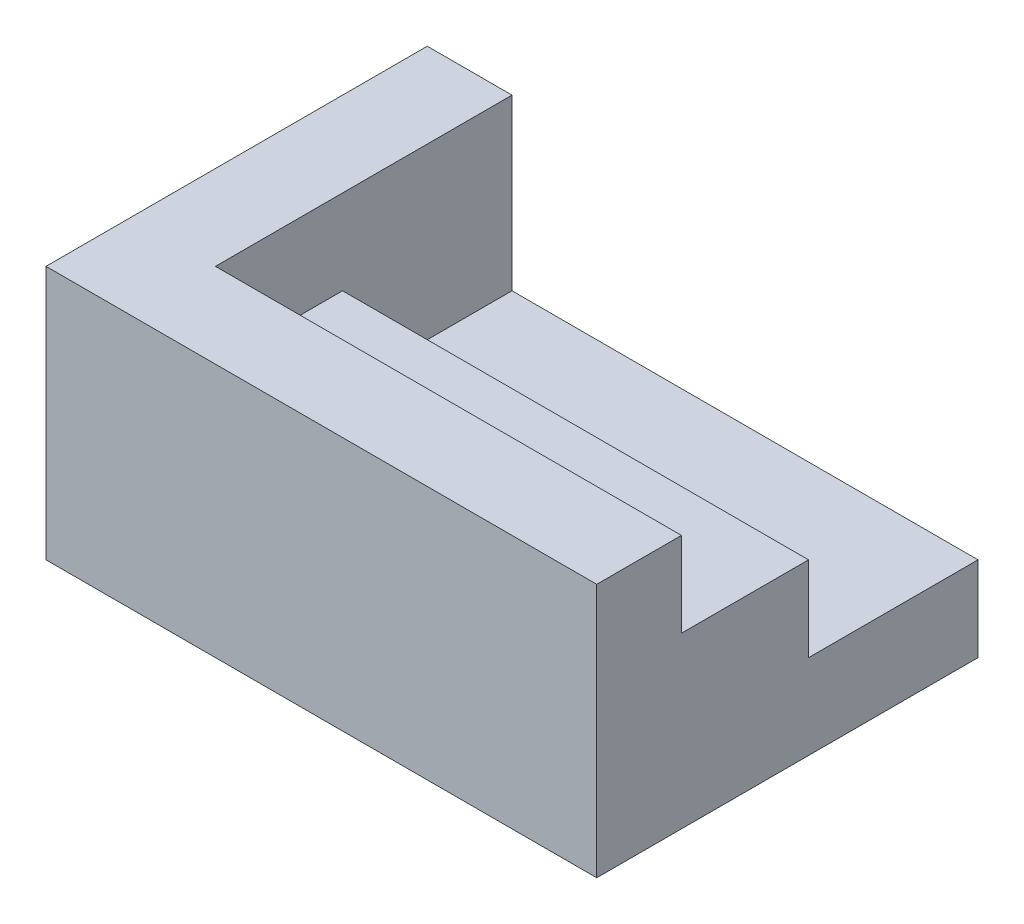
SolidWorks part; units mm, degrees
ref_plane "Front Plane" through (0, 0, 0) normal (0, 0, 1) x (1, 0, 0)
ref_plane "Top Plane" through (0, 0, 0) normal (0, 1, 0) x (1, 0, 0)
ref_plane "Right Plane" through (0, 0, 0) normal (1, 0, 0) x (0, 0, -1)
sketch "Sketch1" plane through (0, 0, 0) normal (0, 1, 0) x (1, 0, 0)
  line L1 (0, 0) -> (104, 0)
  line L2 (0, 0) -> (0, 72)
  line L3 (0, 72) -> (104, 72)
  line L4 (104, 0) -> (104, 72)
  dimension "D1" = 72
  dimension "D2" = 104
extrude "Boss-Extrude1" add sketch "Sketch1" along normal blind 16
sketch "Sketch3" plane through (0, 0, 0) normal (-1, 0, 0) x (0, 0, 1)
  line L1 (0, 0) -> (-16, 0)
  line L2 (0, 0) -> (0, 48)
  line L3 (0, 48) -> (-16, 48)
  line L4 (-16, 0) -> (-16, 48)
  dimension "D1" = 48
  dimension "D2" = 16
extrude "Boss-Extrude2" add sketch "Sketch3" against normal blind 104
sketch "Sketch6" plane through (0, 0, -72) normal (0, 0, -1) x (-1, 0, 0)
  line L1 (0, 0) -> (-16, 0)
  line L2 (0, 0) -> (0, 48)
  line L3 (0, 48) -> (-16, 48)
  line L4 (-16, 0) -> (-16, 48)
  dimension "D1" = 16
  dimension "D2" = 48
extrude "Boss-Extrude3" add sketch "Sketch6" against normal blind 72
sketch "Sketch7" plane through (0, 16, 0) normal (0, 1, 0) x (1, 0, 0)
  line L0 (104, 16) -> (104, 72) construction
  line L1 (16, 16) -> (104, 16)
  line L2 (16, 16) -> (16, 40)
  line L3 (16, 40) -> (104, 40)
  line L4 (104, 16) -> (104, 40)
  dimension "D1" = 24
extrude "Boss-Extrude4" add sketch "Sketch7" along normal blind 16
